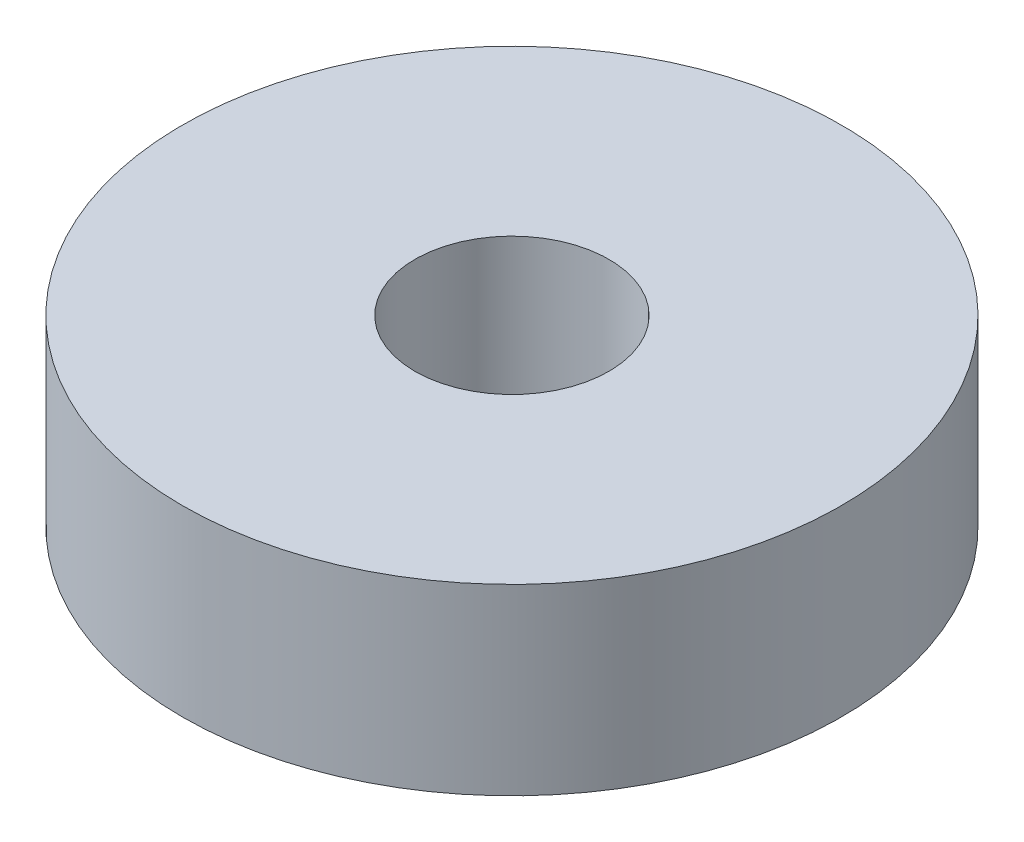
SolidWorks part; units mm, degrees
ref_plane "Front Plane" through (0, 0, 0) normal (0, 0, 1) x (1, 0, 0)
ref_plane "Top Plane" through (0, 0, 0) normal (0, 1, 0) x (1, 0, 0)
ref_plane "Right Plane" through (0, 0, 0) normal (1, 0, 0) x (0, 0, -1)
sketch "Sketch1" plane through (0, 0, 0) normal (0, 1, 0) x (1, 0, 0)
  circle A0 centre (0, 0) radius 9
  dimension "D1" = 18
extrude "Boss-Extrude1" add sketch "Sketch1" along normal blind 5
sketch "Sketch2" plane through (0, 5, 0) normal (0, 1, 0) x (1, 0, 0)
  circle A0 centre (0, 0) radius 2.65
  dimension "D1" = 5.3
extrude "Cut-Extrude1" cut sketch "Sketch2" against normal through all
